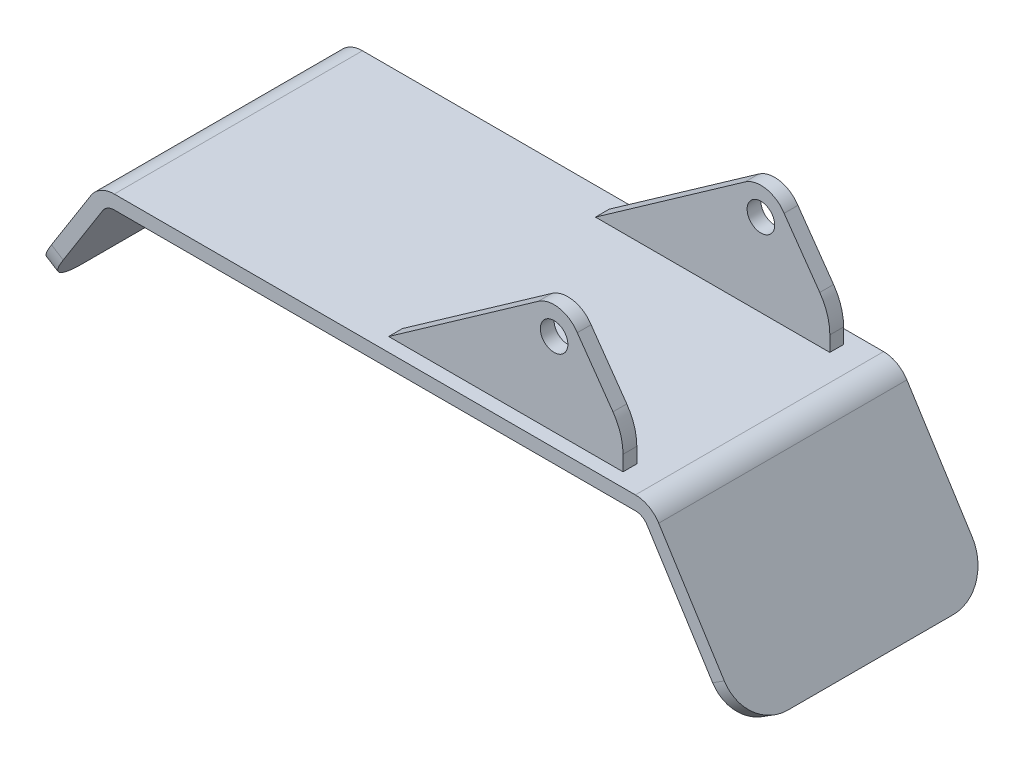
SolidWorks part; units mm, degrees
ref_plane "Front Plane" through (0, 0, 0) normal (0, 0, 1) x (1, 0, 0)
ref_plane "Top Plane" through (0, 0, 0) normal (0, 1, 0) x (1, 0, 0)
ref_plane "Right Plane" through (0, 0, 0) normal (1, 0, 0) x (0, 0, -1)
sketch "Sketch1" plane through (0, 0, 0) normal (0, 0, 1) x (1, 0, 0)
  line L0 (18.8977, 0) -> (-18.8977, 0)
  line L1 (-20.5886, -0.932) -> (-25.0526, -8)
  line L2 (20.5886, -0.932) -> (26.9474, -11)
  line L3 (0, 0) -> (0, -12.508) construction
  line L4 (19.7432, -1.466) -> (26.1019, -11.534)
  line L5 (18.8977, -1) -> (-18.8977, -1)
  line L6 (-19.7432, -1.466) -> (-24.2071, -8.534)
  line L7 (-25.0526, -8) -> (-24.2071, -8.534)
  line L8 (26.9474, -11) -> (26.1019, -11.534)
  arc A0 (-18.8977, 0) -> (-20.5886, -0.932) centre (-18.8977, -2) ccw
  arc A1 (18.8977, 0) -> (20.5886, -0.932) centre (18.8977, -2) cw
  arc A2 (18.8977, -1) -> (19.7432, -1.466) centre (18.8977, -2) cw
  arc A3 (-18.8977, -1) -> (-19.7432, -1.466) centre (-18.8977, -2) ccw
  point P4 (0, 0)
  point P11 (-20, 0)
  point P16 (20, 0)
  dimension "D5" = 2
  dimension "D6" = 2
  dimension "D1" = 40
  dimension "D2" = 52
  dimension "D3" = 8
  dimension "D4" = 11
  dimension "D7" = 1
extrude "Boss-Extrude1" add sketch "Sketch1" along normal mid plane 18
sketch "Sketch3" plane through (0, 0, 0) normal (0, 0, 1) x (1, 0, 0)
  line L0 (0, 0) -> (10.8489, 7.6355)
  line L1 (18.8977, 0) -> (-18.8977, 0) construction
  line L2 (13.6839, 7.0791) -> (16.2711, 3.4032)
  line L3 (17, 1.101) -> (17, 0)
  line L4 (17, 0) -> (0, 0)
  arc A0 (10.8489, 7.6355) -> (13.6839, 7.0791) centre (12, 6) cw
  arc A1 (16.2711, 3.4032) -> (17, 1.101) centre (13, 1.101) cw
  circle A2 centre (12, 6) radius 1
  dimension "D4" = 4
  dimension "D5" = 2
  dimension "D6" = 2
  dimension "D1" = 17
  dimension "D2" = 12
  dimension "D3" = 6
extrude "Boss-Extrude2" add sketch "Sketch3" along normal blind 1 from offset 8 offset against normal yes
mirror "Mirror1" about plane through (0, 0, 0) normal (0, 0, 1) of "Boss-Extrude2"
fillet "Fillet3" radius 3 4 edges at (26.5246, -11.267, 9) (26.5246, -11.267, -9) (-24.6299, -8.267, -9) (-24.6299, -8.267, 9)
